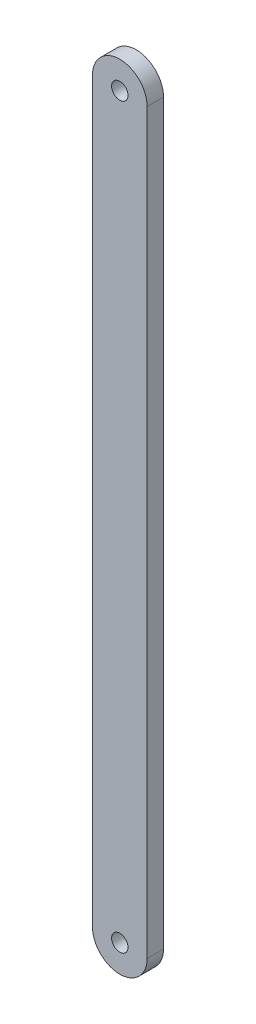
SolidWorks part; units mm, degrees
ref_plane "Front Plane" through (0, 0, 0) normal (0, 0, 1) x (1, 0, 0)
ref_plane "Top Plane" through (0, 0, 0) normal (0, 1, 0) x (1, 0, 0)
ref_plane "Right Plane" through (0, 0, 0) normal (1, 0, 0) x (0, 0, -1)
sketch "Sketch1" plane through (0, 0, 0) normal (0, 0, 1) x (1, 0, 0)
  line L0 (0, 0) -> (0, 270) construction
  line L1 (-10, 0) -> (-10, 270)
  line L2 (10, 0) -> (10, 270)
  arc A0 (-10, 0) -> (10, 0) centre (0, 0) ccw
  arc A1 (10, 270) -> (-10, 270) centre (0, 270) ccw
  point P3 (0, 135)
  dimension "D1" = 10
  dimension "D2" = 270
extrude "Boss-Extrude1" add sketch "Sketch1" along normal blind 6
sketch "Sketch2" plane through (0, 0, 6) normal (0, 0, 1) x (1, 0, 0)
  circle A0 centre (0, 270) radius 3
  circle A1 centre (0, 0) radius 3
  dimension "D1" = 6
extrude "Cut-Extrude1" cut sketch "Sketch2" against normal through all
